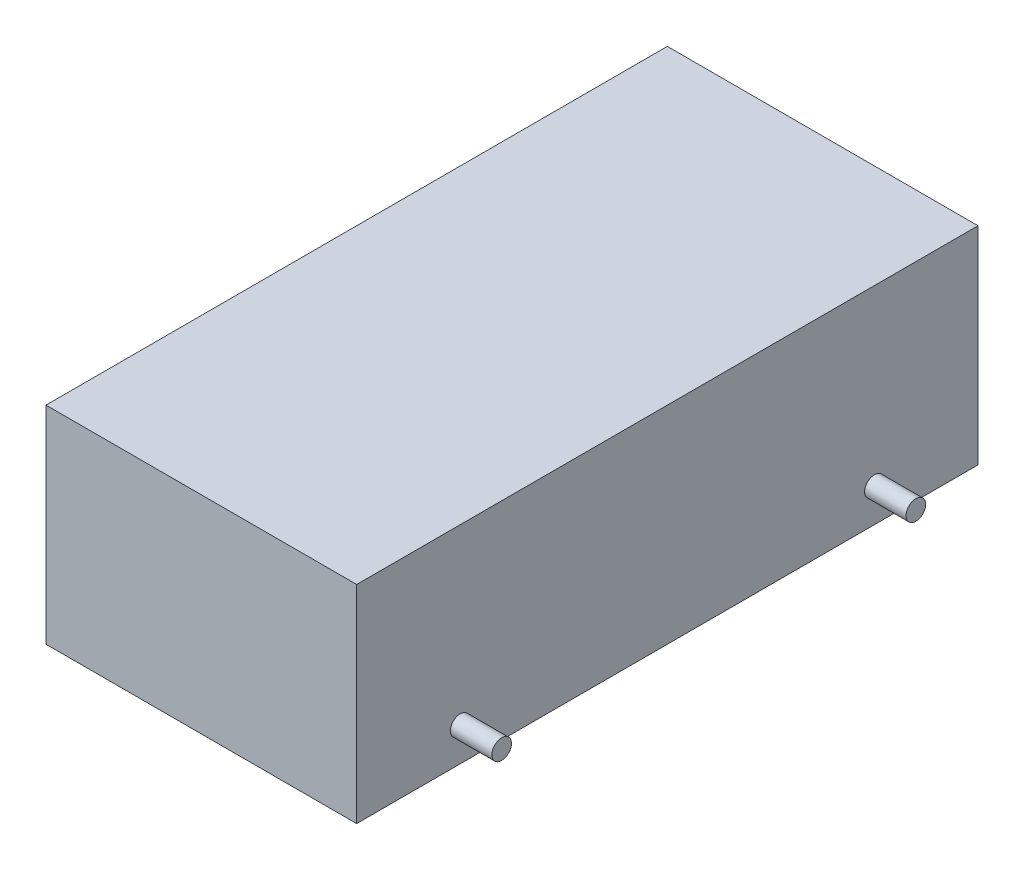
SolidWorks part; units mm, degrees
material "1060 Alloy"
ref_plane "Front Plane" through (0, 0, 0) normal (0, 0, 1) x (1, 0, 0)
ref_plane "Top Plane" through (0, 0, 0) normal (0, 1, 0) x (1, 0, 0)
ref_plane "Right Plane" through (0, 0, 0) normal (1, 0, 0) x (0, 0, -1)
sketch "Sketch1" plane through (0, 0, 0) normal (0, 0, 1) x (1, 0, 0)
  line L0 (-37.5, 25) -> (37.5, -25) construction
  line L1 (-37.5, 25) -> (37.5, 25)
  line L2 (-37.5, 25) -> (-37.5, -25)
  line L3 (-37.5, -25) -> (37.5, -25)
  line L4 (37.5, 25) -> (37.5, -25)
  dimension "D1" = 75
  dimension "D2" = 50
extrude "Boss-Extrude1" add sketch "Sketch1" along normal blind 150
sketch "Sketch2" plane through (37.5, 0, 0) normal (1, 0, 0) x (0, 0, -1)
  line L0 (-125, -16.9192) -> (-25, -16.9192) construction
  line L1 (-150, -25) -> (-150, 25) construction
  line L2 (0, -25) -> (0, 25) construction
  circle A0 centre (-125, -16.9192) radius 2.3696
  circle A1 centre (-25, -16.9192) radius 2.3696
  dimension "D1" = 25
  dimension "D2" = 25
extrude "Boss-Extrude2" add sketch "Sketch2" along normal blind 10
sketch "Sketch3" plane through (-37.5, 0, 0) normal (-1, 0, 0) x (0, 0, 1)
  circle A1 centre (25, -16.9192) radius 2.3696
  circle A2 centre (25, -16.9192) radius 2.3696
  circle A3 centre (125, -16.9192) radius 2.3696
  circle A4 centre (125, -16.9192) radius 2.3696
  dimension "D1" = 0
  dimension "D2" = 0
extrude "Boss-Extrude3" add sketch "Sketch3" along normal blind 10
